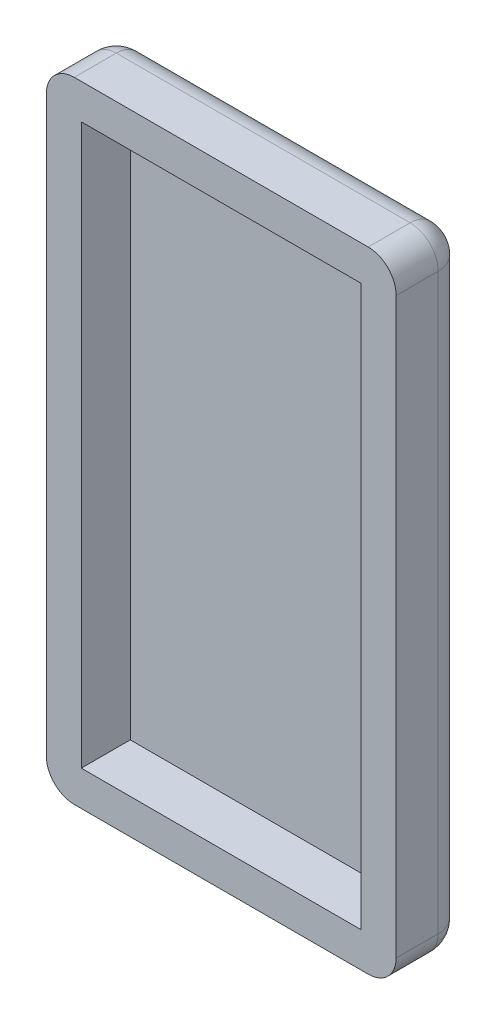
SolidWorks part; units mm, degrees
ref_plane "Ön Düzlem" through (0, 0, 0) normal (0, 0, 1) x (1, 0, 0)
ref_plane "Üst Düzlem" through (0, 0, 0) normal (0, 1, 0) x (1, 0, 0)
ref_plane "Sağ Düzlem" through (0, 0, 0) normal (1, 0, 0) x (0, 0, -1)
ref_plane "Düzlem1" through (0, 0, 5) normal (0, 0, 1) x (1, 0, 0)
sketch "Çizim1" plane through (0, 0, 5) normal (0, 0, 1) x (1, 0, 0)
  line L0 (-13.162, -39.2056) -> (11.838, -39.2056)
  line L1 (11.838, -39.2056) -> (11.838, 5.7944)
  line L2 (11.838, 5.7944) -> (-13.162, 5.7944)
  line L3 (-13.162, 5.7944) -> (-13.162, -39.2056)
extrude "Yükseklik-Ekstrüzyon1" add sketch "Çizim1" against normal blind 5
sketch "Çizim2" plane through (0, 0, 5) normal (0, 0, 1) x (1, 0, 0)
  line L0 (9.338, 3.2944) -> (-10.662, 3.2944)
  line L1 (-10.662, 3.2944) -> (-10.662, -36.7056)
  line L2 (-10.662, -36.7056) -> (9.338, -36.7056)
  line L3 (9.338, -36.7056) -> (9.338, 3.2944)
extrude "Kes-Ekstrüzyon1" cut sketch "Çizim2" against normal blind 3.5
fillet "Radyus1" radius 2 8 edges at (11.838, 5.7944, 2.5) (-0.662, 5.7944, 0) (-13.162, 5.7944, 2.5) (11.838, -16.7056, 0) (-13.162, -39.2056, 2.5) (11.838, -39.2056, 2.5) (-13.162, -16.7056, 0) (-0.662, -39.2056, 0)
